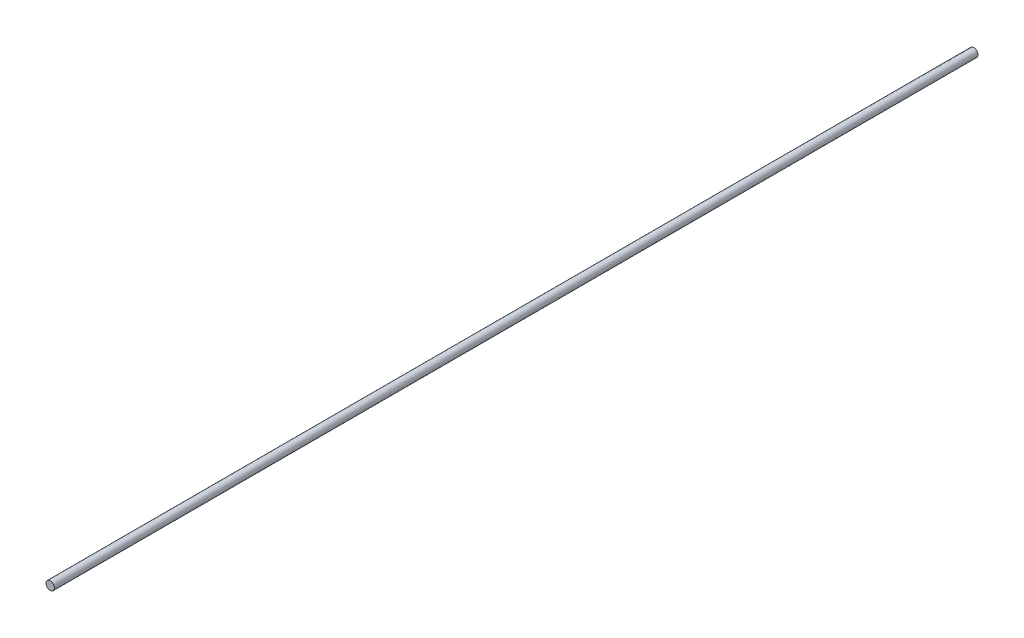
SolidWorks part; units mm, degrees
ref_plane "Front Plane" through (0, 0, 0) normal (0, 0, 1) x (1, 0, 0)
ref_plane "Top Plane" through (0, 0, 0) normal (0, 1, 0) x (1, 0, 0)
ref_plane "Right Plane" through (0, 0, 0) normal (1, 0, 0) x (0, 0, -1)
sketch "Sketch1" plane through (0, 0, 0) normal (0, 0, 1) x (1, 0, 0)
  circle A0 centre (0, 0) radius 1.5
  dimension "D1" = 3
extrude "Boss-Extrude1" add sketch "Sketch1" along normal blind 330.5988
